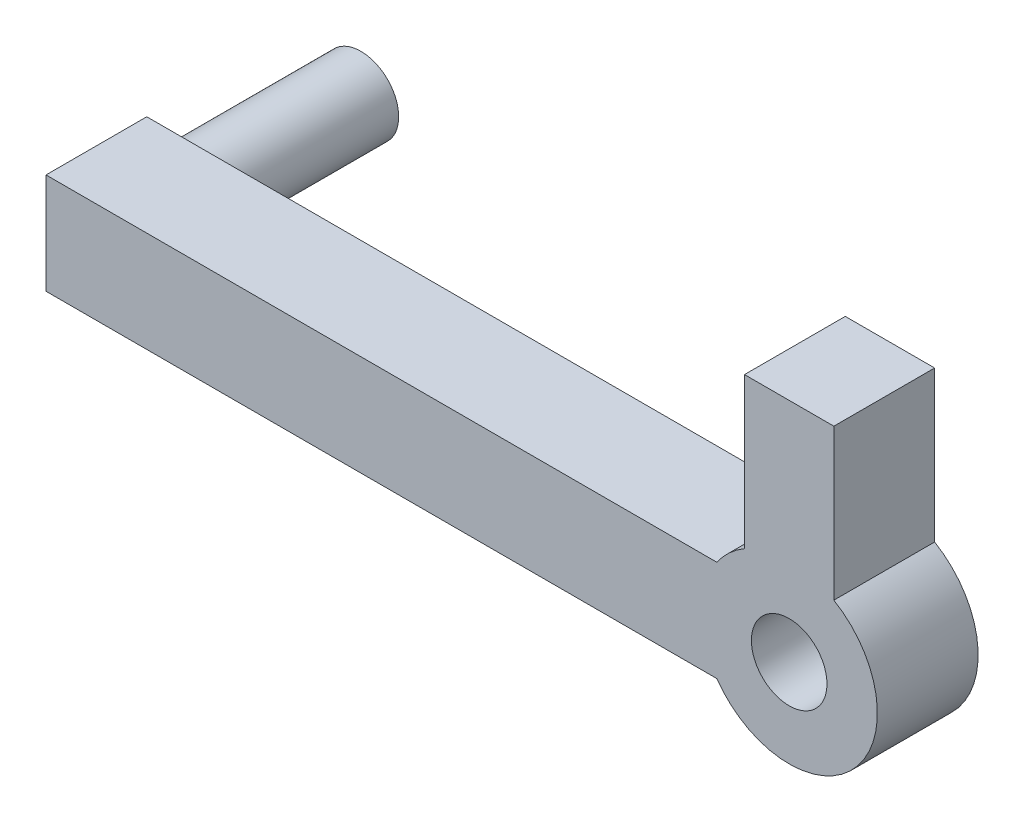
SolidWorks part; units mm, degrees
ref_plane "Front Plane" through (0, 0, 0) normal (0, 0, 1) x (1, 0, 0)
ref_plane "Top Plane" through (0, 0, 0) normal (0, 1, 0) x (1, 0, 0)
ref_plane "Right Plane" through (0, 0, 0) normal (1, 0, 0) x (0, 0, -1)
sketch "Sketch1" plane through (0, 0, 0) normal (0, 0, 1) x (1, 0, 0)
  line L0 (147.5, 17.5) -> (147.5, 20)
  line L1 (0, 0) -> (147.5, 0)
  line L2 (0, 0) -> (0, 20)
  line L3 (0, 20) -> (147.5, 20)
  line L4 (147.5, 0) -> (147.5, 2.5)
  circle A0 centre (147.5, 10) radius 7.5
  circle A1 centre (147.5, 10) radius 17.5
  circle A2 centre (7.5, 10) radius 7.5
  dimension "D2" = 20
  dimension "D3" = 15
  dimension "D4" = 10
  dimension "D5" = 15
  dimension "D6" = 35
  dimension "D1" = 147.5
extrude "Boss-Extrude5" add sketch "Sketch1" along normal blind 20 contours L2 A2 L1 A1 L3 | L3 A1 L1 L4 A0 L0 | A2 | L1 A1 L3 L0 A0 L4
sketch "Sketch2" plane through (0, 0, 0) normal (0, 0, -1) x (-1, 0, 0)
  line L0 (0, 0) -> (0, 20) construction
  circle A0 centre (-7.5, 10) radius 7.5
extrude "Boss-Extrude6" add sketch "Sketch2" along normal blind 35
ref_plane "Plane1" through (0, 25, 0) normal (0, 1, 0) x (1, 0, 0)
sketch "Sketch3" plane through (0, 25, 0) normal (0, 1, 0) x (1, 0, 0)
  line L0 (156.3675, 0) -> (156.3675, -20)
  line L1 (138.6299, 0) -> (156.3675, 0)
  line L3 (138.6299, -20) -> (156.3675, -20)
  line L5 (156.3675, -20) -> (138.6299, -20)
  line L6 (138.6299, -20) -> (138.6299, 0)
extrude "Boss-Extrude7" add sketch "Sketch3" along normal blind 30 contours L6 L3 L0 L1
